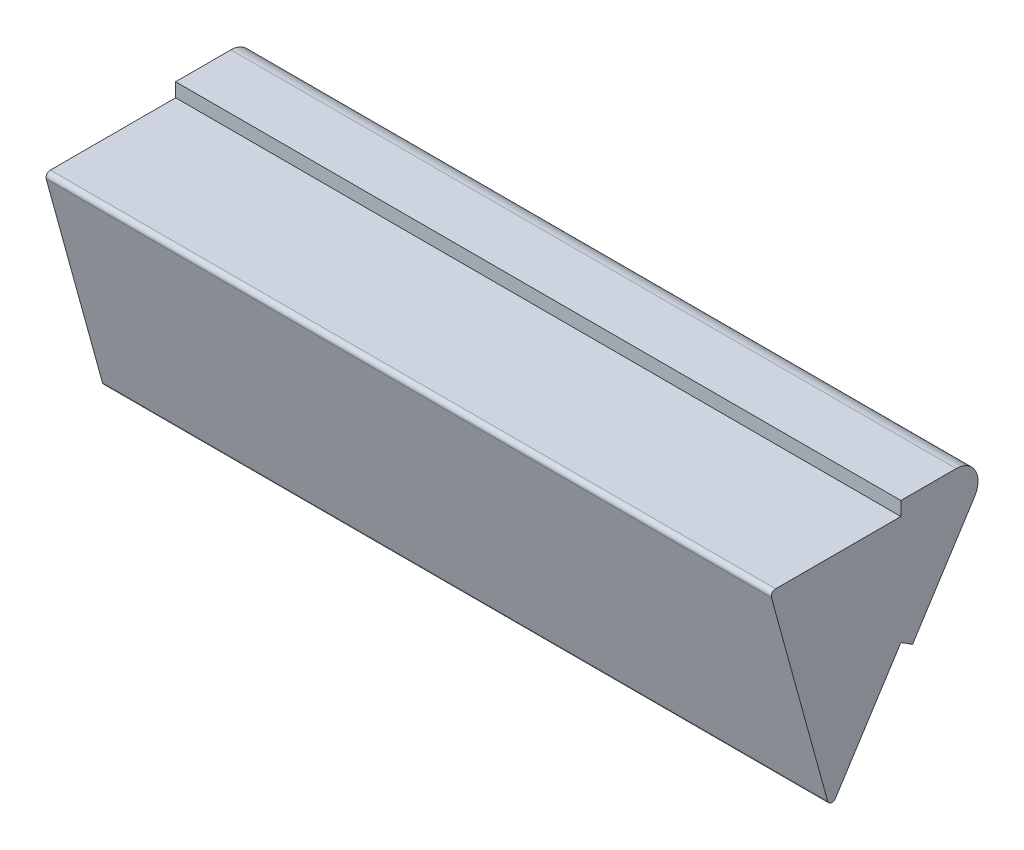
SolidWorks part; units mm, degrees
material "ABS"
ref_plane "Front Plane" through (0, 0, 0) normal (0, 0, 1) x (1, 0, 0)
ref_plane "Top Plane" through (0, 0, 0) normal (0, 1, 0) x (1, 0, 0)
ref_plane "Right Plane" through (0, 0, 0) normal (1, 0, 0) x (0, 0, -1)
sketch "Sketch1" plane through (0, 0, 0) normal (1, 0, 0) x (0, 0, -1)
  line L1 (30, -25) -> (13.8281, -50.2679) construction
  line L2 (0, 0) -> (30, 0) construction
  line L3 (30, -25) -> (13.8281, -50.2679) construction
  line L11 (30, 3.175) -> (51.8021, 3.175) construction
  line L12 (32.6742, -26.7115) -> (51.8021, 3.175) construction
  line L13 (0, 0) -> (13.8281, -50.2679) construction
  line L14 (30, 0) -> (30, 3.175) construction
  line L15 (30, -25) -> (32.6742, -26.7115) construction
  line L16 (1.3122, 0) -> (30, 0)
  line L17 (30, 0) -> (30, 3.175)
  line L18 (30, 3.175) -> (42.6657, 3.175)
  line L19 (46.877, -4.5203) -> (32.6742, -26.7115)
  line L20 (32.6742, -26.7115) -> (30, -25)
  line L21 (30, -25) -> (15.0388, -48.3762)
  line L22 (13.2323, -48.1024) -> (0.348, -1.2652)
  arc A0 (42.6657, 3.175) -> (46.877, -4.5203) centre (42.6657, -1.825) cw
  arc A1 (0.348, -1.2652) -> (1.3122, 0) centre (1.3122, -1) cw
  arc A2 (15.0388, -48.3762) -> (13.2323, -48.1024) centre (14.1965, -47.8371) cw
  dimension "D9" = 5
  dimension "D10" = 1
  dimension "D11" = 1
  dimension "D1" = 30
  dimension "D2" = 3.175
  dimension "D3" = 30
  dimension "D4" = 57.38
  dimension "D5" = 3.175
  dimension "D6" = 35.4836
  dimension "D7" = 21.8021
  dimension "D8" = 57.38
extrude "Boss-Extrude1" add sketch "Sketch1" along normal blind 166.124 contours L19 L20 L21 A2 L22 A1 L16 L17 L18 A0
